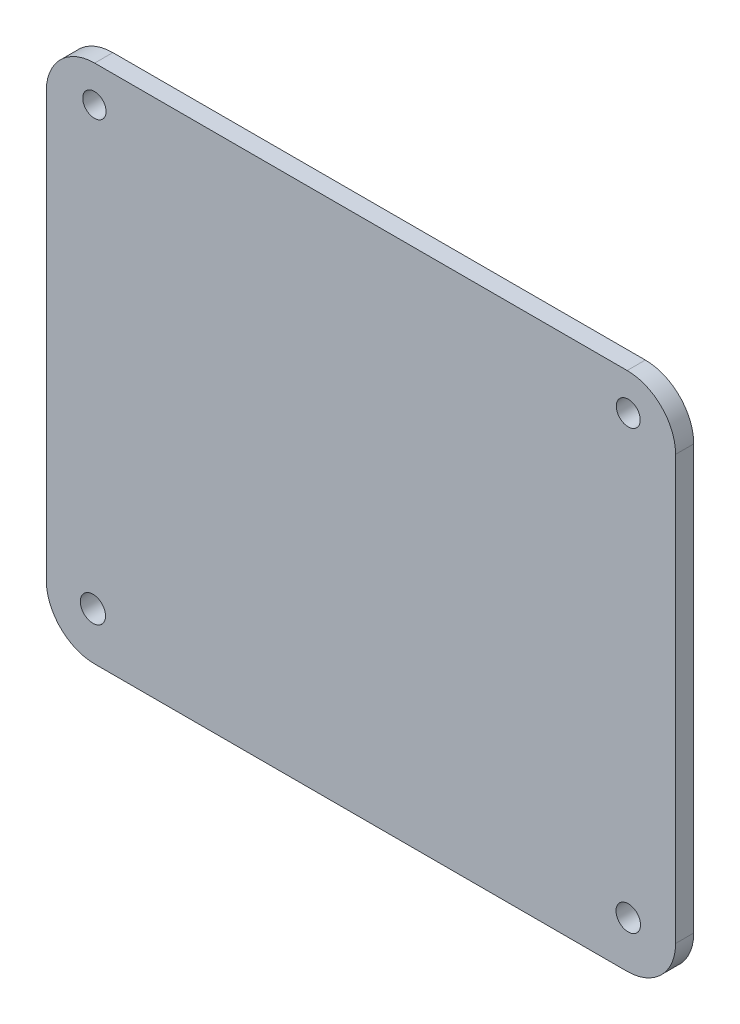
SolidWorks part; units mm, degrees
ref_plane "Front Plane" through (0, 0, 0) normal (0, 0, 1) x (1, 0, 0)
ref_plane "Top Plane" through (0, 0, 0) normal (0, 1, 0) x (1, 0, 0)
ref_plane "Right Plane" through (0, 0, 0) normal (1, 0, 0) x (0, 0, -1)
sketch "Sketch1" plane through (0, 0, 0) normal (0, 0, 1) x (1, 0, 0)
  line L1 (55.88, -54.61) -> (-55.88, -54.61)
  line L2 (66.04, -44.45) -> (66.04, 44.45)
  line L3 (55.88, 54.61) -> (-55.88, 54.61)
  line L4 (-66.04, -44.45) -> (-66.04, 44.45)
  line L5 (66.04, -54.61) -> (-66.04, 54.61) construction
  line L6 (66.04, 54.61) -> (-66.04, -54.61) construction
  arc A0 (-55.88, 54.61) -> (-66.04, 44.45) centre (-55.88, 44.45) ccw
  arc A1 (66.04, 44.45) -> (55.88, 54.61) centre (55.88, 44.45) ccw
  arc A2 (55.88, -54.61) -> (66.04, -44.45) centre (55.88, -44.45) ccw
  arc A3 (-55.88, -54.61) -> (-66.04, -44.45) centre (-55.88, -44.45) cw
  point P0 (0, 0)
  dimension "D3" = 10.16
  dimension "D4" = 10.16
  dimension "D5" = 10.16
  dimension "D6" = 10.16
  dimension "D1" = 109.22
  dimension "D2" = 132.08
extrude "Boss-Extrude1" add sketch "Sketch1" along normal blind 3.81
sketch "Sketch2" plane through (0, 0, 3.81) normal (0, 0, 1) x (1, 0, 0)
  circle A0 centre (-55.9361, 46.99) radius 2.4475
  circle A1 centre (56.106, 46.99) radius 2.5148
  circle A2 centre (56.106, -44.7582) radius 2.5707
  arc A3 (54.0076, -46.2433) -> (57.5911, -42.6598) centre (50.7178, -39.37) ccw construction
  circle A4 centre (-56.2442, -44.7582) radius 2.6491
  arc A5 (-57.7633, -42.5878) -> (-54.0739, -46.2772) centre (-50.8561, -39.37) ccw construction
extrude "Cut-Extrude1" cut sketch "Sketch2" against normal up to next
